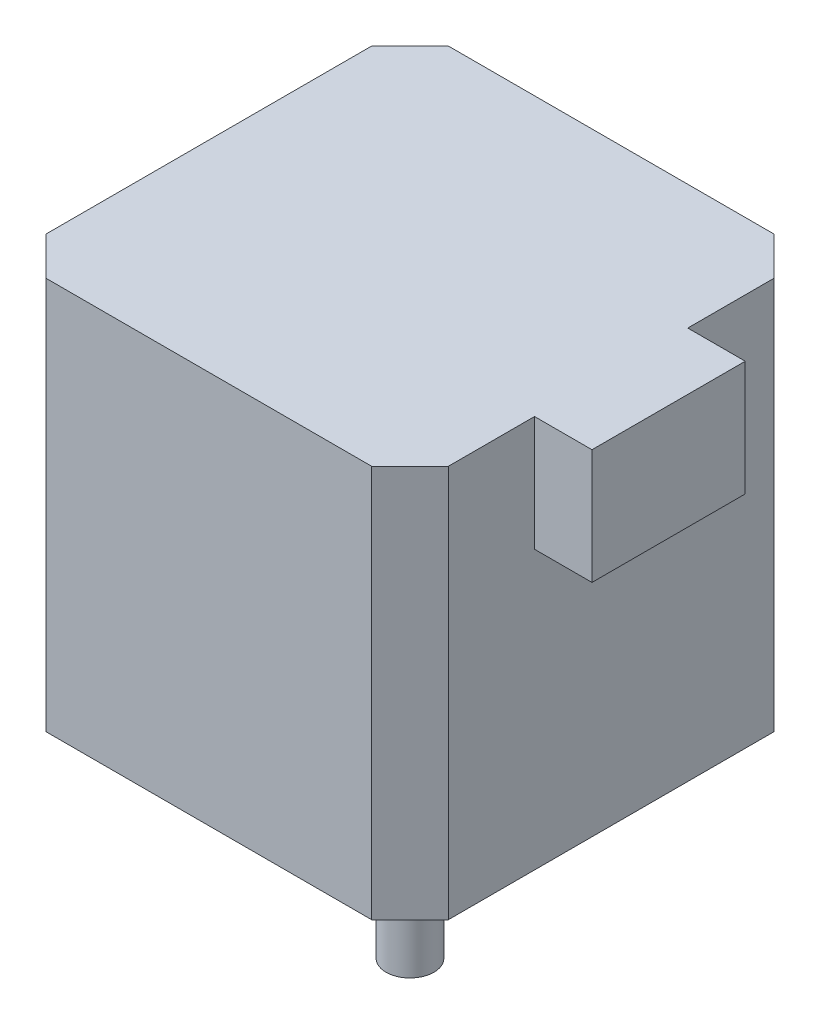
SolidWorks part; units mm, degrees
ref_plane "Front Plane" through (0, 0, 0) normal (0, 0, 1) x (1, 0, 0)
ref_plane "Top Plane" through (0, 0, 0) normal (0, 1, 0) x (1, 0, 0)
ref_plane "Right Plane" through (0, 0, 0) normal (1, 0, 0) x (0, 0, -1)
sketch "Sketch1" plane through (0, 0, 0) normal (0, 1, 0) x (1, 0, 0)
  line L1 (-21, 21) -> (21, 21)
  line L2 (-21, 21) -> (-21, -21)
  line L3 (-21, -21) -> (21, -21)
  line L4 (21, 21) -> (21, -21)
  line L5 (-21, 21) -> (21, -21) construction
  line L6 (-21, -21) -> (21, 21) construction
  point P0 (0, 0)
  dimension "D1" = 42
  dimension "D2" = 42
extrude "Boss-Extrude1" add sketch "Sketch1" along normal blind 41
chamfer "Chamfer1" distance 4 angle 45 4 edges at (-21, 20.5, 21) (-21, 20.5, -21) (21, 20.5, -21) (21, 20.5, 21)
sketch "Sketch2" plane through (0, 0, 0) normal (0, 1, 0) x (1, 0, 0)
  circle A0 centre (0, 0) radius 11
  dimension "D1" = 22
extrude "Boss-Extrude2" add sketch "Sketch2" against normal blind 1.7
sketch "Sketch3" plane through (0, 0, 0) normal (0, 1, 0) x (1, 0, 0)
  circle A0 centre (0, 0) radius 2.5
  dimension "D1" = 5
extrude "Boss-Extrude3" add sketch "Sketch3" against normal blind 22.5
sketch "Sketch4" plane through (21, 0, 0) normal (1, 0, 0) x (0, 0, -1)
  line L0 (0, 23.1) -> (0, -23.1) construction
  line L1 (-8, 29) -> (8, 29)
  line L2 (-8, 29) -> (-8, 41)
  line L3 (-8, 41) -> (8, 41)
  line L4 (8, 29) -> (8, 41)
  line L5 (-8, 29) -> (8, 41) construction
  line L6 (-8, 41) -> (8, 29) construction
  line L7 (-17, 41) -> (17, 41) construction
  point P0 (0, 35)
  dimension "D1" = 12
  dimension "D2" = 16
extrude "Boss-Extrude4" add sketch "Sketch4" along normal blind 6
hole_wizard "Tap Drill for M3 Tap1" positions "Sketch6" profile "Sketch5" hole size "M3" standard "ISO"
sketch "Sketch6" plane through (0, 0, 0) normal (0, -1, 0) x (-1, 0, 0)
  line L0 (0, -21.6) -> (0, 22.2238) construction
  line L1 (0, 23.1) -> (0, -23.1) construction
  line L3 (-27.7581, 0) -> (22.3819, 0) construction
  line L4 (-26.4, 0) -> (26.4, 0) construction
  point P0 (-15.5, -15.5)
  point P17 (15.5, -15.5)
  point P18 (15.5, 15.5)
  point P19 (-15.5, 15.5)
  dimension "D1" = 15.5
  dimension "D2" = 15.5
sketch "Sketch5" plane through (15.5, 0, 15.5) normal (1, 0, 0) x (0, 0, -1)
  line L0 (0, 0) -> (0, 8.7511)
  line L1 (0, 8.7511) -> (1.25, 8)
  line L2 (1.25, 8) -> (1.25, 0)
  line L5 (1.25, 0) -> (0, 0)
  line L10 (0, 8.7511) -> (-1.25, 8) construction
  line L11 (0, -6.35) -> (0, 107.95) construction
  dimension "Hole Dia." = 2.5
  dimension "Hole Depth" = 8
  dimension "Drill Angle" = 118
